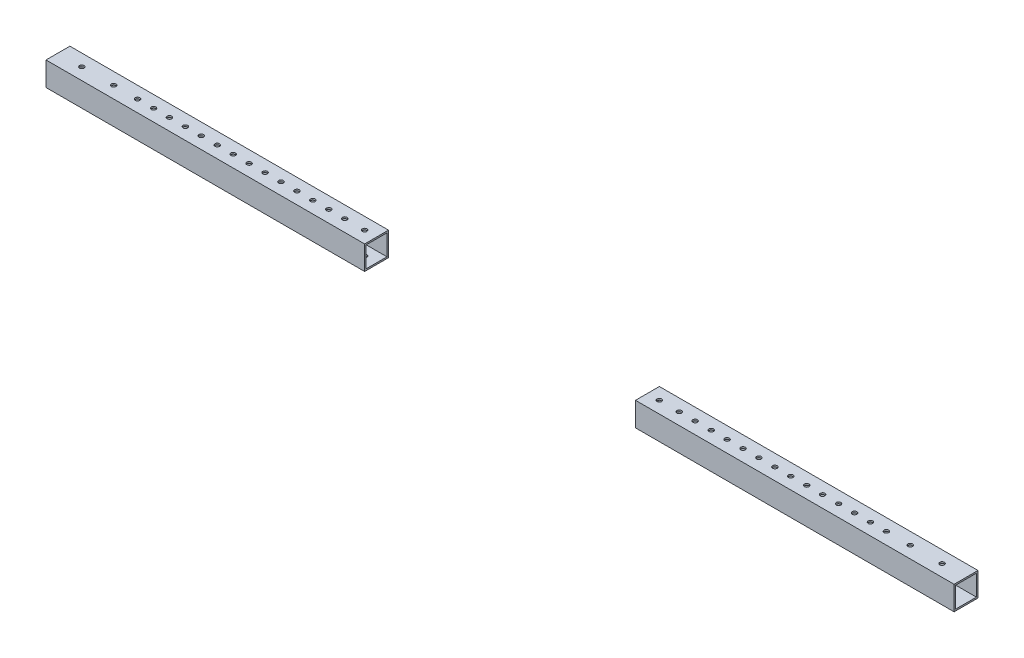
SolidWorks part; units mm, degrees
material "Thornel Mat VMA"
ref_plane "前视基准面" through (0, 0, 0) normal (0, 0, 1) x (1, 0, 0)
ref_plane "上视基准面" through (0, 0, 0) normal (0, 1, 0) x (1, 0, 0)
ref_plane "右视基准面" through (0, 0, 0) normal (1, 0, 0) x (0, 0, -1)
other "Configuration Table"
sketch "草图1" plane through (0, 0, 0) normal (0, 1, 0) x (1, 0, 0)
  line L0 (-285, 0) -> (285, 0)
  dimension "D1" = 570
other "铝管 15X15X1(1)"
ref_plane "基准面1" through (-285, 0, 0) normal (1, 0, 0) x (0, 0, -1)
sketch "草图11" plane through (-285, 0, 0) normal (1, 0, 0) x (0, 0, -1)
  line L1 (-7.5, -7.5) -> (7.5, -7.5)
  line L2 (-7.5, -7.5) -> (-7.5, 7.5)
  line L3 (-7.5, 7.5) -> (7.5, 7.5)
  line L4 (7.5, -7.5) -> (7.5, 7.5)
  line L5 (-7.5, -7.5) -> (7.5, 7.5) construction
  line L6 (-7.5, 7.5) -> (7.5, -7.5) construction
  line L7 (-6.5, -6.5) -> (6.5, -6.5)
  line L8 (-6.5, -6.5) -> (-6.5, 6.5)
  line L9 (-6.5, 6.5) -> (6.5, 6.5)
  line L10 (6.5, -6.5) -> (6.5, 6.5)
  line L11 (-6.5, -6.5) -> (6.5, 6.5) construction
  line L12 (-6.5, 6.5) -> (6.5, -6.5) construction
  point P0 (0, 0)
  point P6 (0, 0)
  point P11 (0, 0)
  dimension "D1" = 15
  dimension "D2" = 15
  dimension "D3" = 13
  dimension "D4" = 13
sketch "草图12" plane through (0, 7.5, 0) normal (0, 1, 0) x (1, 0, 0)
  line L0 (-285, 0) -> (285, 0) construction
  line L1 (-285, 7.5) -> (-285, -7.5) construction
  line L2 (0, 7.5) -> (0, -7.5) construction
  line L3 (285, 7.5) -> (-285, 7.5) construction
  line L4 (285, -7.5) -> (-285, -7.5) construction
  circle A0 centre (-270, 0) radius 1.45
  circle A1 centre (-250, 0) radius 1.45
  circle A2 centre (250, 0) radius 1.45
  circle A3 centre (270, 0) radius 1.45
  dimension "D1" = 2.9
  dimension "D3" = 2.9
  dimension "D4" = 20
  dimension "D2" = 15
extrude "切除-拉伸1" cut sketch "草图12" against normal through all
sketch "草图13" plane through (0, 0, -7.5) normal (0, 0, -1) x (-1, 0, 0)
  line L0 (0, 7.5) -> (0, -7.5) construction
  line L1 (-285, 7.5) -> (285, 7.5) construction
  line L2 (-285, -7.5) -> (285, -7.5) construction
  line L3 (285, 0) -> (-285, 0) construction
  circle A0 centre (-18.5, 0) radius 1.45
  circle A1 centre (18.5, 0) radius 1.45
  dimension "D1" = 2.9
  dimension "D2" = 2.9
  dimension "D3" = 18.5
  dimension "D4" = 18.5
extrude "切除-拉伸2" cut sketch "草图13" against normal through all
sketch "草图15" plane through (0, -7.5, 0) normal (0, -1, 0) x (1, 0, 0)
  line L1 (-85, -7.5) -> (85, -7.5)
  line L2 (-85, -7.5) -> (-85, 7.5)
  line L3 (-85, 7.5) -> (85, 7.5)
  line L4 (85, -7.5) -> (85, 7.5)
  line L5 (-85, -7.5) -> (85, 7.5) construction
  line L6 (-85, 7.5) -> (85, -7.5) construction
  point P0 (0, 0)
  dimension "D1" = 15
  dimension "D2" = 170
extrude "切除-拉伸4" cut sketch "草图15" against normal through all
sketch "草图16" plane through (0, -7.5, 0) normal (0, -1, 0) x (1, 0, 0)
  line L0 (-285, 0) -> (285, 0) construction
  line L1 (85, -7.5) -> (85, 7.5) construction
  line L2 (0, 0) -> (0, 17.9409) construction
  circle A0 centre (105, 0) radius 1.45
  circle A1 centre (115, 0) radius 1.45
  circle A2 centre (125, 0) radius 1.45
  circle A3 centre (135, 0) radius 1.45
  circle A4 centre (145, 0) radius 1.45
  circle A5 centre (155, 0) radius 1.45
  circle A6 centre (165, 0) radius 1.45
  circle A7 centre (175, 0) radius 1.45
  circle A8 centre (185, 0) radius 1.45
  circle A9 centre (195, 0) radius 1.45
  circle A10 centre (205, 0) radius 1.45
  circle A11 centre (215, 0) radius 1.45
  circle A12 centre (225, 0) radius 1.45
  circle A13 centre (235, 0) radius 1.45
  circle A16 centre (-235, 0) radius 1.45
  circle A17 centre (-225, 0) radius 1.45
  circle A18 centre (-215, 0) radius 1.45
  circle A19 centre (-205, 0) radius 1.45
  circle A20 centre (-195, 0) radius 1.45
  circle A21 centre (-185, 0) radius 1.45
  circle A22 centre (-175, 0) radius 1.45
  circle A23 centre (-165, 0) radius 1.45
  circle A24 centre (-155, 0) radius 1.45
  circle A25 centre (-145, 0) radius 1.45
  circle A26 centre (-135, 0) radius 1.45
  circle A27 centre (-125, 0) radius 1.45
  circle A28 centre (-115, 0) radius 1.45
  circle A29 centre (-105, 0) radius 1.45
  circle A30 centre (245, 0) radius 1.45 [skipped]
  circle A31 centre (92.5, 0) radius 1.45
  circle A32 centre (-92.5, 0) radius 1.45
  dimension "D1" = 2.9
  dimension "D3" = 15
  dimension "D5" = 2.9
  dimension "D6" = 7.5
  dimension "D2" = 20
  dimension "D4" = 10
extrude "切除-拉伸5" cut sketch "草图16" against normal through all
